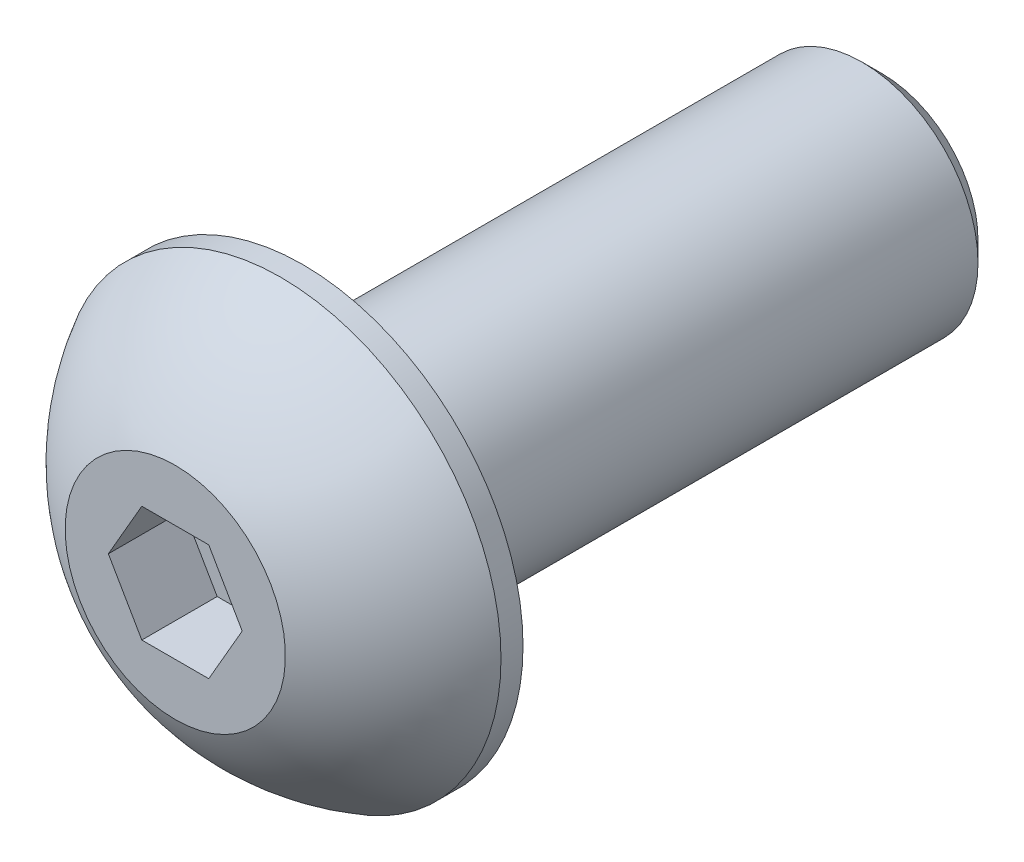
SolidWorks part; units mm, degrees
material "AISI 304"
ref_plane "Front Plane" through (0, 0, 0) normal (0, 0, 1) x (1, 0, 0)
ref_plane "Top Plane" through (0, 0, 0) normal (0, 1, 0) x (1, 0, 0)
ref_plane "Right Plane" through (0, 0, 0) normal (1, 0, 0) x (0, 0, -1)
sketch "Sketch1" plane through (0, 0, 0) normal (1, 0, 0) x (0, 0, -1)
  line L0 (-0.38, 3.8) -> (0, 3.8)
  line L1 (0, 3.8) -> (0, 2)
  line L2 (0, 2) -> (10, 2)
  line L3 (10, 2) -> (10, 0)
  line L4 (10, 0) -> (-2.2, 0) construction
  line L5 (-2.2, 0) -> (-2.2, 1.9)
  line L6 (10, 0) -> (-2.2, 0)
  arc A0 (-0.38, 3.8) -> (-2.2, 1.9) centre (1.6853, 0) ccw
  dimension "SIZE" = 4
  dimension "D2" = 3.8
  dimension "A" = 7.6
  dimension "S" = 0.38
  dimension "H" = 2.2
  dimension "L" = 10
revolve "Revolve1" add sketch "Sketch1" angle 360 mid plane about L4
cosmetic thread "Cosmetic Thread1"
sketch "Sketch2" plane through (0, 0, 2.2) normal (0, 0, 1) x (1, 0, 0)
  line L1 (1.1547, 0) -> (0.5774, 1)
  line L2 (0.5774, 1) -> (-0.5774, 1)
  line L3 (-0.5774, 1) -> (-1.1547, 0)
  line L4 (-1.1547, 0) -> (-0.5774, -1)
  line L5 (-0.5774, -1) -> (0.5774, -1)
  line L6 (0.5774, -1) -> (1.1547, 0)
  circle A0 centre (0, 0) radius 1 construction
  dimension "J" = 2
extrude "Cut-Extrude1" cut sketch "Sketch2" against normal blind 1.3
chamfer "Chamfer1" distance 0.35 angle 45 1 edges at (0, 2, -10)
fillet "Fillet1" radius 0.2 1 edges at (0, 2, 0)
